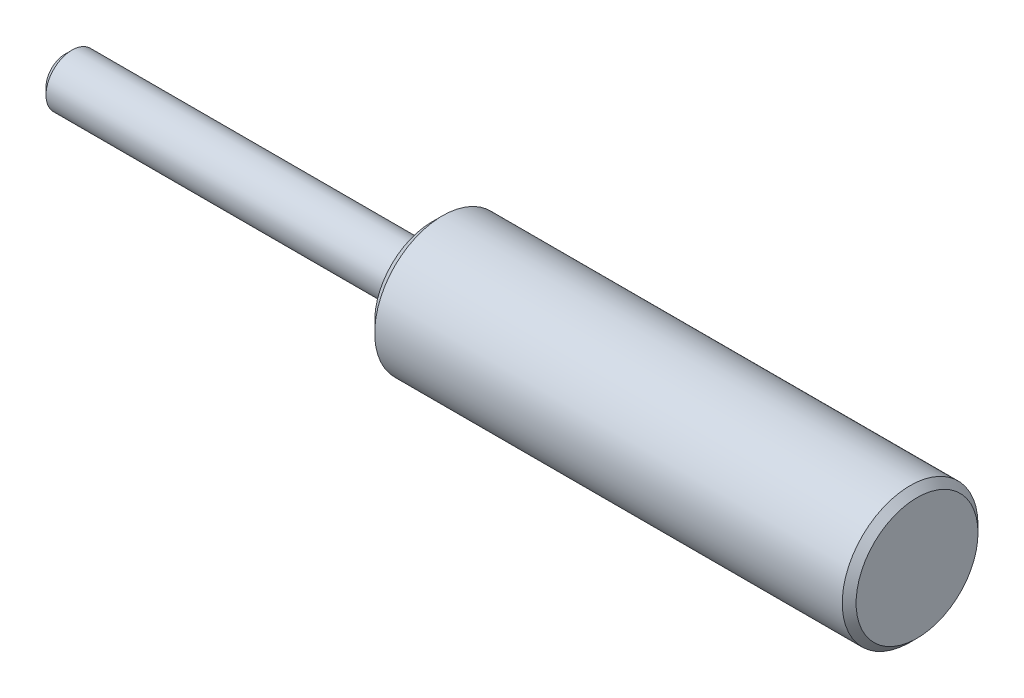
SolidWorks part; units mm, degrees
ref_plane "前视基准面" through (0, 0, 0) normal (0, 0, 1) x (1, 0, 0)
ref_plane "上视基准面" through (0, 0, 0) normal (0, 1, 0) x (1, 0, 0)
ref_plane "右视基准面" through (0, 0, 0) normal (1, 0, 0) x (0, 0, -1)
sketch "草图1" plane through (0, 0, 0) normal (1, 0, 0) x (0, 0, -1)
  circle A0 centre (0, 0) radius 9.8
  dimension "D1" = 19.6
extrude "凸台-拉伸1" add sketch "草图1" along normal blind 70
sketch "草图2" plane through (0, 0, 0) normal (-1, 0, 0) x (0, 0, 1)
  circle A0 centre (0, 0) radius 3.75
  dimension "D1" = 7.5
extrude "凸台-拉伸2" add sketch "草图2" along normal blind 53
chamfer "倒角1" distance 1.5 angle 45 1 edges at (0, 0, -9.8)
chamfer "倒角2" distance 1 angle 45 1 edges at (-53, 0, 3.75)
chamfer "倒角3" distance 1 angle 45 1 edges at (70, 0, -9.8)
